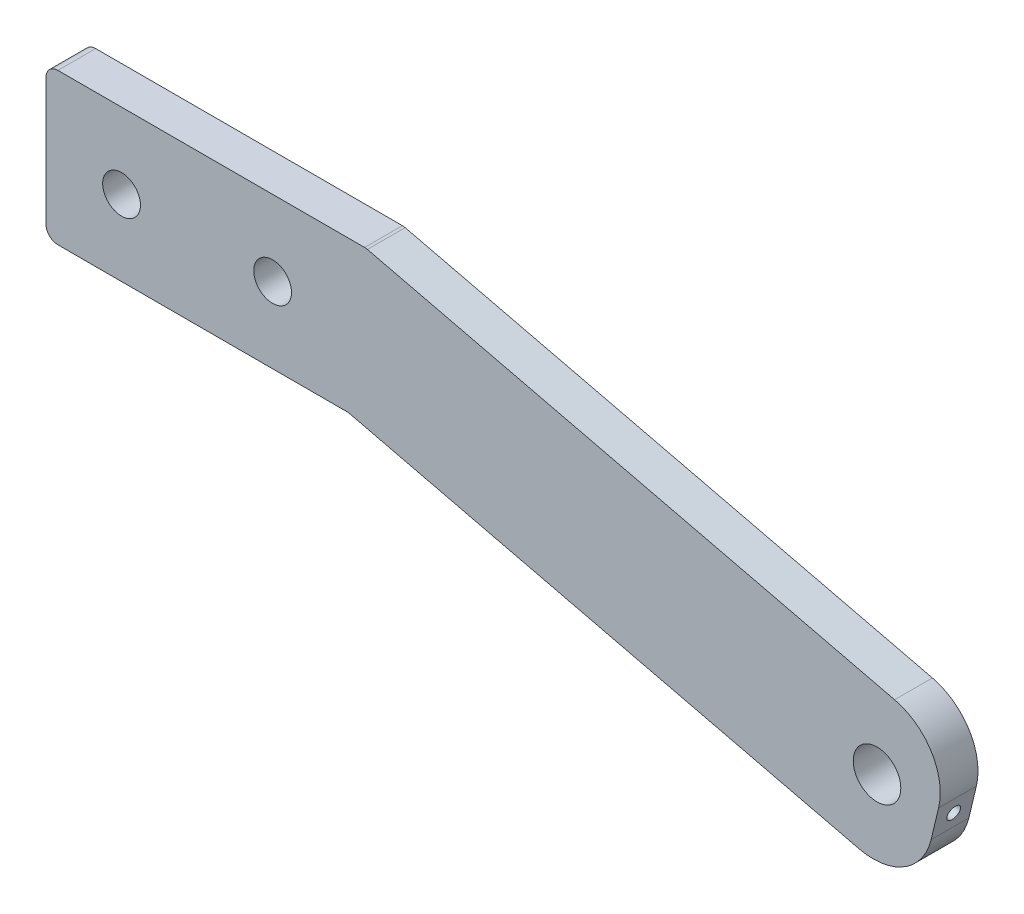
SolidWorks part; units mm, degrees
ref_plane "Front Plane" through (0, 0, 0) normal (0, 0, 1) x (1, 0, 0)
ref_plane "Top Plane" through (0, 0, 0) normal (0, 1, 0) x (1, 0, 0)
ref_plane "Right Plane" through (0, 0, 0) normal (1, 0, 0) x (0, 0, -1)
sketch "Sketch1" plane through (0, 0, 0) normal (0, 0, 1) x (1, 0, 0)
  line L0 (-25.4, 0) -> (-38.1, 0) construction
  line L2 (-38.1, -12.7) -> (-38.1, 12.7)
  line L5 (104.5604, -8.5999) -> (98.6396, -33.3001) construction
  line L6 (12.7, -12.7) -> (71.3084, -26.7487) construction
  line L19 (-25.4, 0) -> (0, 0) construction
  line L25 (15.7017, 12.7) -> (-38.1, 12.7)
  line L26 (12.7, -12.7) -> (-38.1, -12.7)
  line L27 (15.7017, 12.7) -> (74.6646, -1.4337) construction
  line L28 (15.7017, 12.7) -> (114.2849, -10.9309)
  line L29 (12.7, -12.7) -> (108.3641, -35.6312)
  line L30 (108.3641, -35.6312) -> (114.2849, -10.9309)
  circle A0 centre (-25.4, 0) radius 3.175
  circle A12 centre (0, 0) radius 3.175
  circle A13 centre (101.6, -20.95) radius 4
  point P8 (0, 0)
  point P16 (64.2348, -43.9487)
  point P17 (0, 0)
  dimension "D4" = 6.35
  dimension "D7" = 10
  dimension "D8" = 25.4
  dimension "D5" = 101.6
  dimension "D6" = 20.95
  dimension "D9" = 8
  dimension "D2" = 50.8
  dimension "D3" = 12.7
  dimension "D12" = 25.4
  dimension "D13" = 25.4
extrude "Boss-Extrude1" add sketch "Sketch1" along normal blind 6.35
sketch "Sketch3" plane through (110.5529, -26.5001, 0) normal (0.9725, -0.2331, 0) x (0, 0, -1)
  line L0 (-6.35, 3.3102) -> (0, 3.3102) construction
  line L1 (-6.35, -9.3898) -> (-6.35, 16.0102) construction
  line L2 (0, -9.3898) -> (0, 16.0102) construction
  circle A0 centre (-3.175, 3.3102) radius 1.1303
  dimension "D1" = 2.2606
extrude "Cut-Extrude2" cut sketch "Sketch3" against normal up to next
fillet "Fillet4" radius 10 2 edges at (108.3641, -35.6312, 3.175) (114.2849, -10.9309, 3.175)
sketch "Sketch4" plane through (0, 0, 0) normal (0, 0, 1) x (1, 0, 0)
  line L0 (-15.875, -3.175) -> (-15.875, 3.175)
  line L1 (-15.875, -3.175) -> (-9.525, -3.175)
  line L2 (-15.875, 3.175) -> (-9.525, 3.175)
  line L3 (-9.525, -3.175) -> (-9.525, 3.175)
  line L4 (-15.875, -3.175) -> (-9.525, 3.175) construction
  line L5 (-15.875, 3.175) -> (-9.525, -3.175) construction
  line L6 (-25.4, 0) -> (0, 0) construction
  line L7 (0, 0) -> (24.101, 0) construction
  line L8 (9.525, -3.175) -> (9.525, 3.175)
  line L9 (9.525, -3.175) -> (28.575, -3.175)
  line L10 (9.525, 3.175) -> (28.575, 3.175)
  line L11 (28.575, -3.175) -> (28.575, 3.175)
  line L12 (9.525, -3.175) -> (28.575, 3.175) construction
  line L13 (9.525, 3.175) -> (28.575, -3.175) construction
  circle A1 centre (-25.4, 0) radius 3.175 construction
  point P1 (-12.7, 0)
  point P11 (0, 0)
  point P14 (19.05, 0)
  dimension "D2" = 9.525
  dimension "D1" = 6.35
  dimension "D3" = 9.525
  dimension "D4" = 19.05
extrude "Boss-Extrude2" add sketch "Sketch4" against normal blind 4.7625
fillet "Fillet3" radius 2 12 edges at (-38.1, -12.7, 3.175) (-38.1, 12.7, 3.175) (12.7, -12.7, 3.175) (15.7017, 12.7, 3.175) (28.575, -3.175, -2.3813) (28.575, 3.175, -2.3813) (9.525, 3.175, -2.3813) (9.525, -3.175, -2.3813) (-9.525, 3.175, -2.3813) (-9.525, -3.175, -2.3813) (-15.875, -3.175, -2.3813) (-15.875, 3.175, -2.3813)
